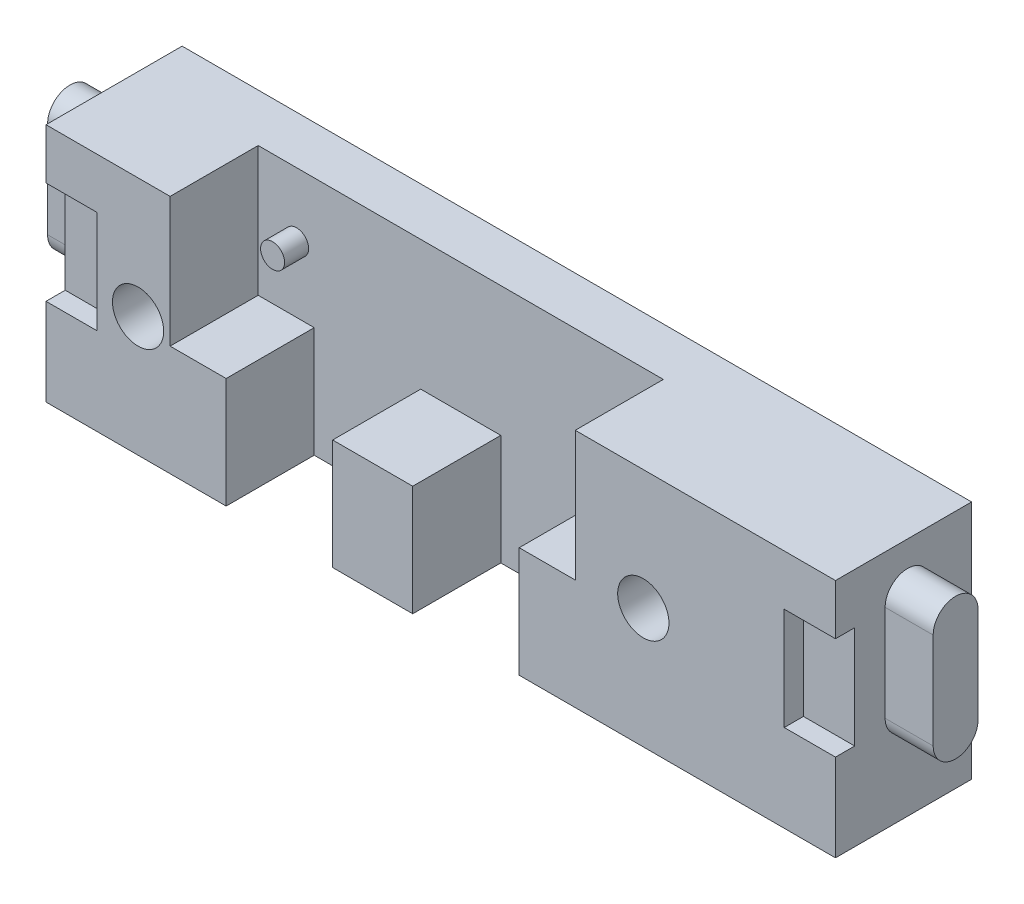
SolidWorks part; units mm, degrees
material "ABS"
ref_plane "前视基准面" through (0, 0, 0) normal (0, 0, 1) x (1, 0, 0)
ref_plane "上视基准面" through (0, 0, 0) normal (0, 1, 0) x (1, 0, 0)
ref_plane "右视基准面" through (0, 0, 0) normal (1, 0, 0) x (0, 0, -1)
other "Configuration Table"
sketch "草图1" plane through (0, 0, 0) normal (0, 0, 1) x (1, 0, 0)
  line L6 (0, 0) -> (49.3, 0)
  line L7 (0, 0) -> (0, 15)
  line L8 (0, 15) -> (49.3, 15)
  line L9 (49.3, 0) -> (49.3, 15)
  dimension "D1" = 49.3
  dimension "D2" = 15
extrude "凸台-拉伸1" add sketch "草图1" along normal blind 3
sketch "草图2" plane through (0, 0, 3) normal (0, 0, 1) x (1, 0, 0)
  line L0 (0, 15) -> (49.3, 15) construction
  line L1 (7.75, 15) -> (33.05, 15)
  line L2 (7.75, 15) -> (7.75, 6.9)
  line L3 (7.75, 6.9) -> (33.05, 6.9)
  line L4 (33.05, 15) -> (33.05, 6.9)
  line L5 (17.9, 4.5675) -> (22.9, 4.5675) construction
  line L6 (11.25, 6.9) -> (17.9, 6.9)
  line L7 (22.9, 6.9) -> (29.55, 6.9)
  line L8 (22.9, 6.9) -> (22.9, 0)
  line L9 (0, 0) -> (49.3, 0)
  line L10 (49.3, 0) -> (49.3, 15)
  line L11 (49.3, 15) -> (0, 15)
  line L12 (0, 15) -> (0, 0)
  line L13 (0, 0) -> (49.3, 0)
  line L14 (49.3, 0) -> (49.3, 15)
  line L15 (49.3, 15) -> (0, 15)
  line L16 (0, 15) -> (0, 0)
  line L17 (22.9, 0) -> (29.55, 0)
  line L18 (29.55, 6.9) -> (29.55, 0)
  line L19 (11.25, 6.9) -> (11.25, 0)
  line L20 (11.25, 0) -> (17.9, 0)
  line L21 (17.9, 6.9) -> (17.9, 0)
  point P20 (20.4, 4.5675)
  point P21 (20.4, 6.9)
  line M7 (0, 0) -> (49.3, 0)
  line M8 (49.3, 0) -> (49.3, 15)
  line M9 (49.3, 15) -> (0, 15)
  line M10 (0, 15) -> (0, 0)
  dimension "D1" = 25.3
  dimension "D2" = 8.1
  dimension "D4" = 5
  dimension "D5" = 6.65
  dimension "D6" = 6.65
  dimension "D7" = 7.75
  dimension "D3" = 0
extrude "凸台-拉伸2" add sketch "草图2" along normal blind 5.5 contours L19 L3 L2 M9 M10 M7 | L5 L21 L8 M7 | L21 L5 L8 L3 | L3 L18 L13 L4 M8 M9
sketch "草图3" plane through (0, 0, 3) normal (0, 0, 1) x (1, 0, 0)
  line L2 (7.75, 15) -> (7.75, 6.9) construction
  line L3 (7.75, 6.9) -> (11.25, 6.9) construction
  circle A0 centre (10.15, 11) radius 0.75
  circle A1 centre (30.65, 11) radius 0.75
  dimension "D1" = 1.5
  dimension "D2" = 1.5
  dimension "D3" = 20.5
  dimension "D4" = 2.4
  dimension "D5" = 4.1
extrude "凸台-拉伸3" add sketch "草图3" along normal blind 1.5
sketch "草图4" plane through (0, 0, 8.5) normal (0, 0, 1) x (1, 0, 0)
  line L0 (7.75, 15) -> (0, 15) construction
  line L1 (0, 15) -> (0, 0) construction
  line L2 (49.3, 15) -> (33.05, 15) construction
  line L3 (49.3, 0) -> (49.3, 15) construction
  circle A0 centre (3.875, 7.5) radius 1
  circle A1 centre (41.175, 7.5) radius 1
  point P8 (3.875, 15)
  point P11 (0, 7.5)
  point P15 (41.175, 15)
  point P18 (49.3, 7.5)
  dimension "D1" = 2
  dimension "D2" = 2
extrude "切除-拉伸1" cut sketch "草图4" against normal blind 10
sketch "草图5" plane through (0, 0, 0) normal (0, 0, -1) x (-1, 0, 0)
  line L1 (-5.0008, 9.45) -> (-6.1267, 7.5)
  line L2 (-6.1267, 7.5) -> (-5.0008, 5.55)
  line L3 (-5.0008, 5.55) -> (-2.7492, 5.55)
  line L4 (-2.7492, 5.55) -> (-1.6233, 7.5)
  line L5 (-1.6233, 7.5) -> (-2.7492, 9.45)
  line L6 (-2.7492, 9.45) -> (-5.0008, 9.45)
  line L7 (-42.3008, 9.45) -> (-43.4267, 7.5)
  line L8 (-43.4267, 7.5) -> (-42.3008, 5.55)
  line L9 (-42.3008, 5.55) -> (-40.0492, 5.55)
  line L10 (-40.0492, 5.55) -> (-38.9233, 7.5)
  line L11 (-38.9233, 7.5) -> (-40.0492, 9.45)
  line L12 (-40.0492, 9.45) -> (-42.3008, 9.45)
  circle A0 centre (-3.875, 7.5) radius 1.95 construction
  circle A1 centre (-41.175, 7.5) radius 1.95 construction
  point P10 (-3.875, 5.55)
  dimension "D1" = 3.9
  dimension "D2" = 3.9
extrude "切除-拉伸2" cut sketch "草图5" against normal blind 4
sketch "草图6" plane through (0, 0, 0) normal (-1, 0, 0) x (0, 0, 1)
  line L0 (4, 6) -> (4, 12) construction
  line L1 (2.6, 6) -> (2.6, 12)
  line L2 (5.4, 6) -> (5.4, 12)
  line L3 (0, 0) -> (0, 15) construction
  line L4 (8.5, 15) -> (0, 15) construction
  arc A0 (2.6, 6) -> (5.4, 6) centre (4, 6) ccw
  arc A1 (5.4, 12) -> (2.6, 12) centre (4, 12) ccw
  point P2 (4, 9)
  dimension "D4" = 3
  dimension "D1" = 6
  dimension "D2" = 2.8
  dimension "D3" = 4
extrude "凸台-拉伸4" add sketch "草图6" along normal blind 3
ref_plane "基准面1" through (24.65, 0, 0) normal (-1, 0, 0) x (0, 0, 1)
mirror "镜向1" about plane through (24.65, 0, 0) normal (-1, 0, 0) of "凸台-拉伸4"
sketch "草图7" plane through (0, 0, 8.5) normal (0, 0, 1) x (1, 0, 0)
  line L0 (0, 15) -> (0, 0) construction
  line L1 (0, 11.65) -> (3, 11.65)
  line L2 (0, 11.65) -> (0, 5.65)
  line L3 (0, 5.65) -> (3, 5.65)
  line L4 (3, 11.65) -> (3, 5.65)
  line L5 (7.75, 15) -> (0, 15) construction
  dimension "D1" = 3.35
  dimension "D2" = 6
  dimension "D3" = 3
sketch "草图9" plane through (0, 0, 8.5) normal (0, 0, 1) x (1, 0, 0)
  circle A0 centre (41.175, 7.5) radius 1 construction
  circle A1 centre (3.875, 7.5) radius 1 construction
  circle A2 centre (41.175, 7.5) radius 1
  circle A3 centre (3.875, 7.5) radius 1
extrude "凸台-拉伸5" add sketch "草图9" against normal up to surface (4.5 mm away) up to face at (41.175, 7.5, 4)
sketch "草图10" plane through (0, 0, 0) normal (0, 0, -1) x (-1, 0, 0)
  line L0 (-2.7492, 9.45) -> (-5.0008, 9.45) construction
  line L1 (-5.0008, 9.45) -> (-6.1267, 7.5) construction
  line L2 (-6.1267, 7.5) -> (-5.0008, 5.55) construction
  line L3 (-5.0008, 5.55) -> (-2.7492, 5.55) construction
  line L4 (-2.7492, 5.55) -> (-1.6233, 7.5) construction
  line L5 (-1.6233, 7.5) -> (-2.7492, 9.45) construction
  line L6 (-40.0492, 9.45) -> (-42.3008, 9.45) construction
  line L7 (-42.3008, 9.45) -> (-43.4267, 7.5) construction
  line L8 (-43.4267, 7.5) -> (-42.3008, 5.55) construction
  line L9 (-42.3008, 5.55) -> (-40.0492, 5.55) construction
  line L10 (-40.0492, 5.55) -> (-38.9233, 7.5) construction
  line L11 (-38.9233, 7.5) -> (-40.0492, 9.45) construction
  line L12 (-2.7492, 9.45) -> (-5.0008, 9.45)
  line L13 (-5.0008, 9.45) -> (-6.1267, 7.5)
  line L14 (-6.1267, 7.5) -> (-5.0008, 5.55)
  line L15 (-5.0008, 5.55) -> (-2.7492, 5.55)
  line L16 (-2.7492, 5.55) -> (-1.6233, 7.5)
  line L17 (-1.6233, 7.5) -> (-2.7492, 9.45)
  line L18 (-40.0492, 9.45) -> (-42.3008, 9.45)
  line L19 (-42.3008, 9.45) -> (-43.4267, 7.5)
  line L20 (-43.4267, 7.5) -> (-42.3008, 5.55)
  line L21 (-42.3008, 5.55) -> (-40.0492, 5.55)
  line L22 (-40.0492, 5.55) -> (-38.9233, 7.5)
  line L23 (-38.9233, 7.5) -> (-40.0492, 9.45)
extrude "凸台-拉伸9" add sketch "草图10" against normal up to surface (4 mm away) contours L18 L19 L20 L21 L22 L23
sketch "草图8" plane through (0, 0, 8.5) normal (0, 0, 1) x (1, 0, 0)
  line L0 (3, 11.65) -> (3, 5.65) construction
  line L1 (7.75, 15) -> (0, 15) construction
  line L2 (49.3, 6) -> (49.3, 12) construction
  circle A0 centre (5.75, 7.5) radius 2.75 construction
  circle A1 centre (5.75, 7.5) radius 1.6
  circle A2 centre (37.3, 7.5) radius 1.6
  dimension "D1" = 5.5
  dimension "D2" = 3.2
  dimension "D4" = 3.2
  dimension "D3" = 7.5
  dimension "D5" = 12
extrude "切除-拉伸3" cut sketch "草图8" against normal through all
sketch "草图11" plane through (0, 0, 0) normal (0, 0, -1) x (-1, 0, 0)
  line L1 (-37.3, 10.6177) -> (-40, 9.0588)
  line L2 (-40, 9.0588) -> (-40, 5.9412)
  line L3 (-40, 5.9412) -> (-37.3, 4.3823)
  line L4 (-37.3, 4.3823) -> (-34.6, 5.9412)
  line L5 (-34.6, 5.9412) -> (-34.6, 9.0588)
  line L6 (-34.6, 9.0588) -> (-37.3, 10.6177)
  line L7 (-5.75, 10.6177) -> (-8.45, 9.0588)
  line L8 (-8.45, 9.0588) -> (-8.45, 5.9412)
  line L9 (-8.45, 5.9412) -> (-5.75, 4.3823)
  line L10 (-5.75, 4.3823) -> (-3.05, 5.9412)
  line L11 (-3.05, 5.9412) -> (-3.05, 9.0588)
  line L12 (-3.05, 9.0588) -> (-5.75, 10.6177)
  circle A0 centre (-37.3, 7.5) radius 2.7 construction
  circle A1 centre (-5.75, 7.5) radius 2.7 construction
  dimension "D1" = 5.4
extrude "切除-拉伸4" cut sketch "草图11" against normal blind 2.3
sketch "草图12" plane through (0, 0, 8.5) normal (0, 0, 1) x (1, 0, 0)
sketch "草图13" plane through (0, 0, 8.5) normal (0, 0, 1) x (1, 0, 0)
  line L12 (0, 15) -> (0, 0) construction
  line L13 (0, 11.85) -> (3.2, 11.85)
  line L14 (0, 11.85) -> (0, 5.45)
  line L15 (0, 5.45) -> (3.2, 5.45)
  line L16 (3.2, 11.85) -> (3.2, 5.45)
  line L17 (0, 11.65) -> (3, 11.65) construction
  line L18 (0, 5.65) -> (3, 5.65) construction
  line L19 (3, 11.65) -> (3, 5.65) construction
  dimension "D1" = 0.2
  dimension "D2" = 0.2
  dimension "D3" = 0.2
extrude "切除-拉伸5" cut sketch "草图13" against normal blind 1.2
mirror "镜向2" about plane through (24.65, 0, 0) normal (-1, 0, 0) of "切除-拉伸5"
equation "\"5。5\"=10"
